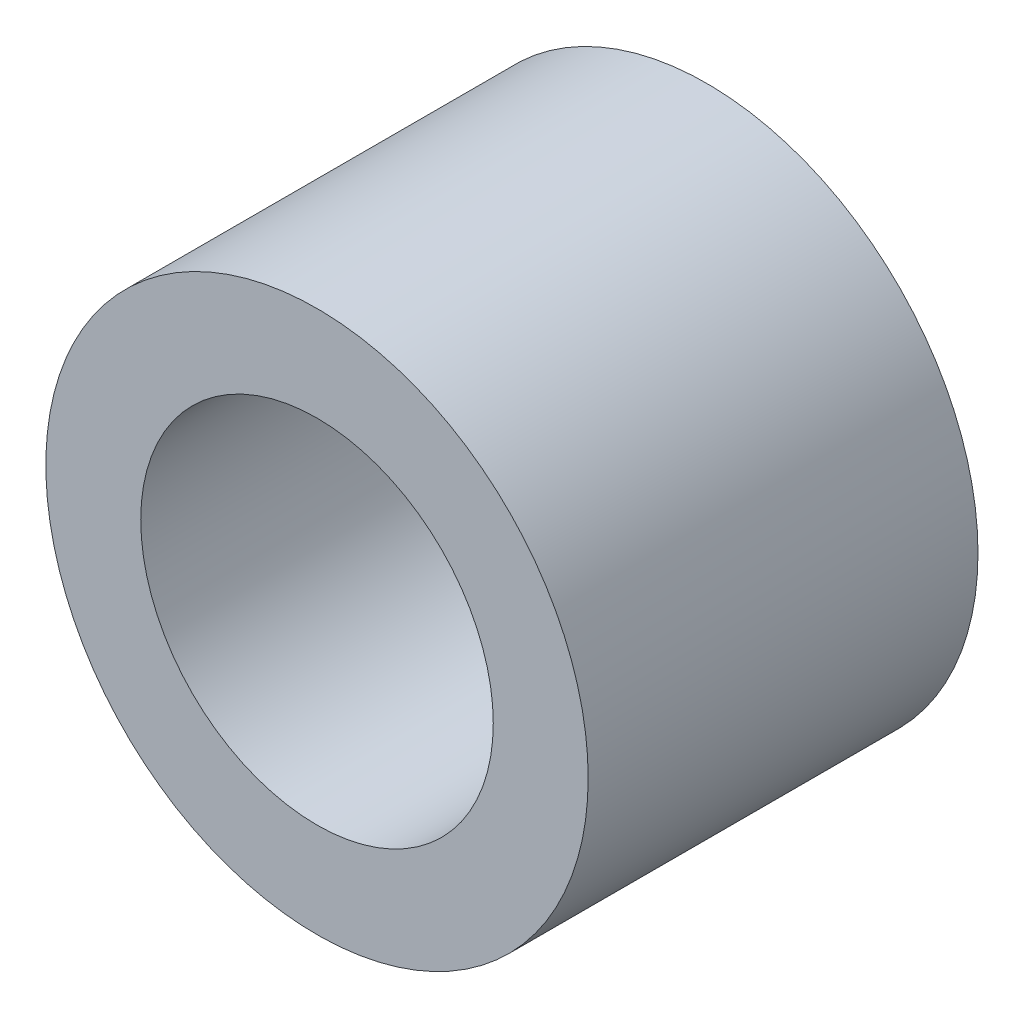
SolidWorks part; units mm, degrees
ref_plane "前视基准面" through (0, 0, 0) normal (0, 0, 1) x (1, 0, 0)
ref_plane "上视基准面" through (0, 0, 0) normal (0, 1, 0) x (1, 0, 0)
ref_plane "右视基准面" through (0, 0, 0) normal (1, 0, 0) x (0, 0, -1)
sketch "草图1" plane through (0, 0, 0) normal (0, 0, 1) x (1, 0, 0)
  circle A0 centre (0, 0) radius 2.6
  circle A1 centre (0, 0) radius 4
  dimension "D1" = 5.2
  dimension "D2" = 8
extrude "凸台-拉伸1" add sketch "草图1" along normal blind 5.75
